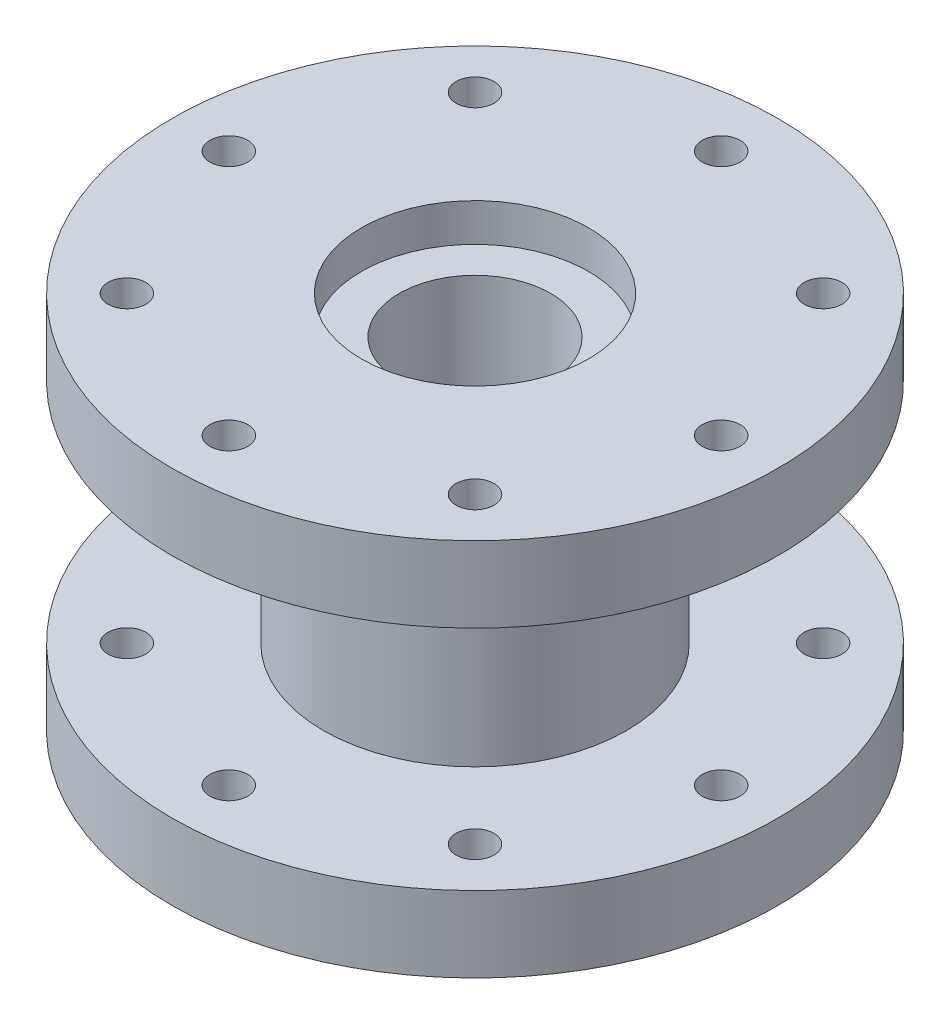
SolidWorks part; units mm, degrees
ref_plane "Front Plane" through (0, 0, 0) normal (0, 0, 1) x (1, 0, 0)
ref_plane "Top Plane" through (0, 0, 0) normal (0, 1, 0) x (1, 0, 0)
ref_plane "Right Plane" through (0, 0, 0) normal (1, 0, 0) x (0, 0, -1)
sketch "Sketch1" plane through (0, 0, 0) normal (0, 0, 1) x (1, 0, 0)
  line L0 (0, 117.3286) -> (0, -47.6033) construction
  line L13 (12.7, 57.15) -> (12.7, 6.35)
  line L14 (12.7, 6.35) -> (19.05, 6.35)
  line L15 (19.05, 6.35) -> (19.05, 0)
  line L16 (19.05, 0) -> (50.8, 0)
  line L17 (50.8, 0) -> (50.8, 12.7)
  line L18 (50.8, 12.7) -> (25.4, 12.7)
  line L19 (25.4, 12.7) -> (25.4, 50.8)
  line L20 (25.4, 50.8) -> (50.8, 50.8)
  line L21 (50.8, 50.8) -> (50.8, 63.5)
  line L22 (50.8, 63.5) -> (19.05, 63.5)
  line L23 (19.05, 63.5) -> (19.05, 57.15)
  line L24 (19.05, 57.15) -> (12.7, 57.15)
  dimension "D1" = 12.7
  dimension "D2" = 50.8
  dimension "D3" = 6.35
  dimension "D4" = 6.35
  dimension "D5" = 25.4
  dimension "D6" = 19.05
  dimension "D7" = 50.8
revolve "Revolve1" add sketch "Sketch1" angle 360 about L0
sketch "Sketch2" plane through (0, 63.5, 0) normal (0, 1, 0) x (1, 0, 0)
  line L0 (0, 0) -> (55.4975, 0) construction
  line L1 (0, 0) -> (41.275, 0) construction
  circle A0 centre (0, 0) radius 41.275
  circle A2 centre (41.275, 0) radius 3.175
  circle A3 centre (29.1858, -29.1858) radius 3.175
  circle A4 centre (0, -41.275) radius 3.175
  circle A5 centre (-29.1858, -29.1858) radius 3.175
  circle A6 centre (-41.275, 0) radius 3.175
  circle A7 centre (-29.1858, 29.1858) radius 3.175
  circle A8 centre (0, 41.275) radius 3.175
  circle A9 centre (29.1858, 29.1858) radius 3.175
  dimension "D1" = 82.55
  dimension "D2" = 6.35
  dimension "D4" = 41.275
  dimension "D3" = 8
extrude "Cut-Extrude2" cut sketch "Sketch2" against normal through all contours A0 A7 | A0 A7 | A0 A8 | A0 A8 | A0 A9 | A0 A9 | A0 A2 | A0 A3 | A0 A3 | A0 A4 | A0 A5 | A0 A6
